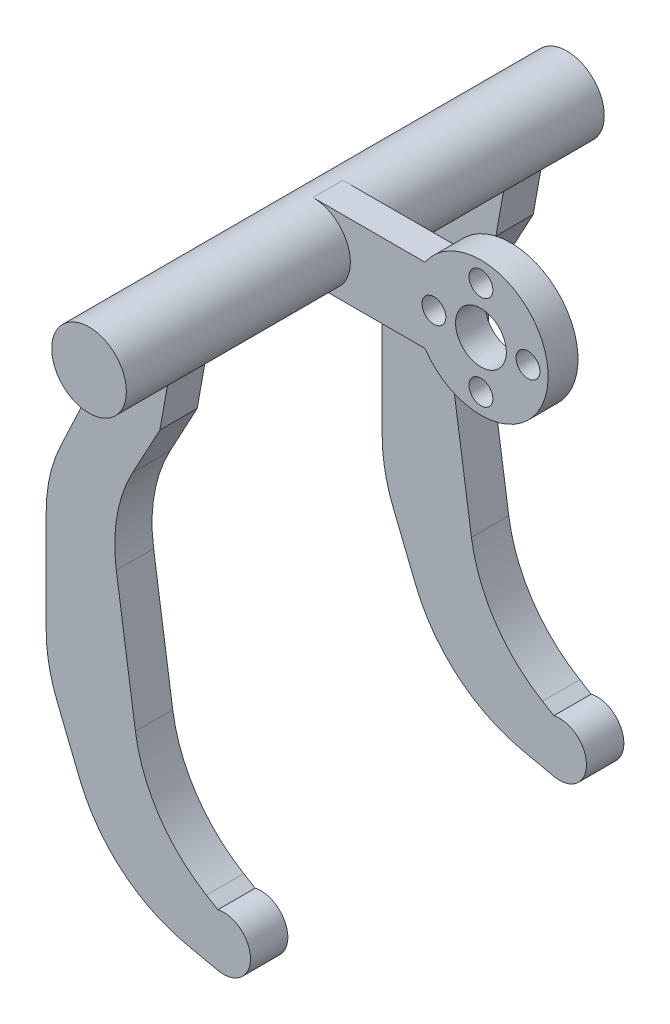
SolidWorks part; units mm, degrees
ref_plane "Front Plane" through (0, 0, 0) normal (0, 0, 1) x (1, 0, 0)
ref_plane "Top Plane" through (0, 0, 0) normal (0, 1, 0) x (1, 0, 0)
ref_plane "Right Plane" through (0, 0, 0) normal (1, 0, 0) x (0, 0, -1)
sketch "Sketch2" plane through (0, 0, 0) normal (0, 0, 1) x (1, 0, 0)
  circle A0 centre (0, 0) radius 11.43
  dimension "D1" = 22.86
extrude "Boss-Extrude1" add sketch "Sketch2" along normal blind 5.08
sketch "Sketch4" plane through (0, 0, 0) normal (0, 0, -1) x (-1, 0, 0)
  circle A0 centre (0, 0) radius 4.318
  circle A1 centre (0, -8.001) radius 2.032
  dimension "D1" = 8.001
extrude "Cut-Extrude1" cut sketch "Sketch4" against normal blind 5.08
sketch "Sketch7" plane through (0, 0, 0) normal (0, 0, -1) x (-1, 0, 0)
  line L1 (9.5038, 6.35) -> (28.5538, 6.35)
  line L2 (9.5038, 6.35) -> (9.5038, -6.35)
  line L3 (9.5038, -6.35) -> (28.5538, -6.35)
  circle A0 centre (0, 0) radius 11.43 construction
  arc A1 (28.5538, 6.35) -> (28.5538, -6.35) centre (28.5538, 0) cw
  dimension "D1" = 12.7
  dimension "D2" = 19.05
  dimension "D3" = 6.35
extrude "Boss-Extrude2" add sketch "Sketch7" against normal blind 5.08
pattern_circular "CirPattern1" count 4 over 360 about axis through (0, 0, 0) along (0, 0, 1) of "Cut-Extrude1"
sketch "Sketch9" plane through (0, 0, 5.08) normal (0, 0, 1) x (1, 0, 0)
  circle A0 centre (-28.5538, 0) radius 6.35
extrude "Boss-Extrude3" add sketch "Sketch9" along normal blind 38.1 and the other way blind 43.18
ref_plane "Plane1" through (0, 0, -31.75) normal (0, 0, 1) x (1, 0, 0)
ref_plane "Plane2" through (-27.94, 0, 0) normal (1, 0, 0) x (0, 0, -1)
sketch "Sketch12" plane through (0, 0, -31.75) normal (0, 0, 1) x (1, 0, 0)
  line L0 (-33.0479, 0) -> (-25.3788, 0)
  line L1 (-33.0479, 0) -> (-47.2674, -30.2454)
  line L2 (-47.2674, -58.3342) -> (-36.5753, -84.8679)
  line L3 (-36.5753, -84.8679) -> (-18.0737, -88.9)
  line L4 (-18.0737, -79.96) -> (-30.3458, -72.6081)
  line L5 (-30.3458, -72.6081) -> (-36.5753, -30.2454)
  line L6 (-47.2674, -30.2454) -> (-47.2674, -58.3342)
  line L7 (-27.94, -12.573) -> (-27.94, 12.573) construction
  line L8 (-27.94, -14.2497) -> (-25.3788, 0)
  line L10 (-36.5753, -30.2454) -> (-27.94, -14.2497)
  line L11 (-25.3788, 0) -> (-25.652, -0.0259)
  arc A0 (-18.0737, -88.9) -> (-18.0737, -79.96) centre (-17.0995, -84.43) ccw
extrude "Boss-Extrude4" add sketch "Sketch12" along normal blind 6.35
fillet "Fillet1" radius 25.4 5 edges at (-36.5753, -30.2454, -28.575) (-30.3458, -72.6081, -28.575) (-36.5753, -84.8679, -28.575) (-47.2674, -58.3342, -28.575) (-47.2674, -30.2454, -28.575)
mirror "Mirror1" about plane through (0, 0, 0) normal (0, 0, 1) of "Fillet1", "Boss-Extrude4"
